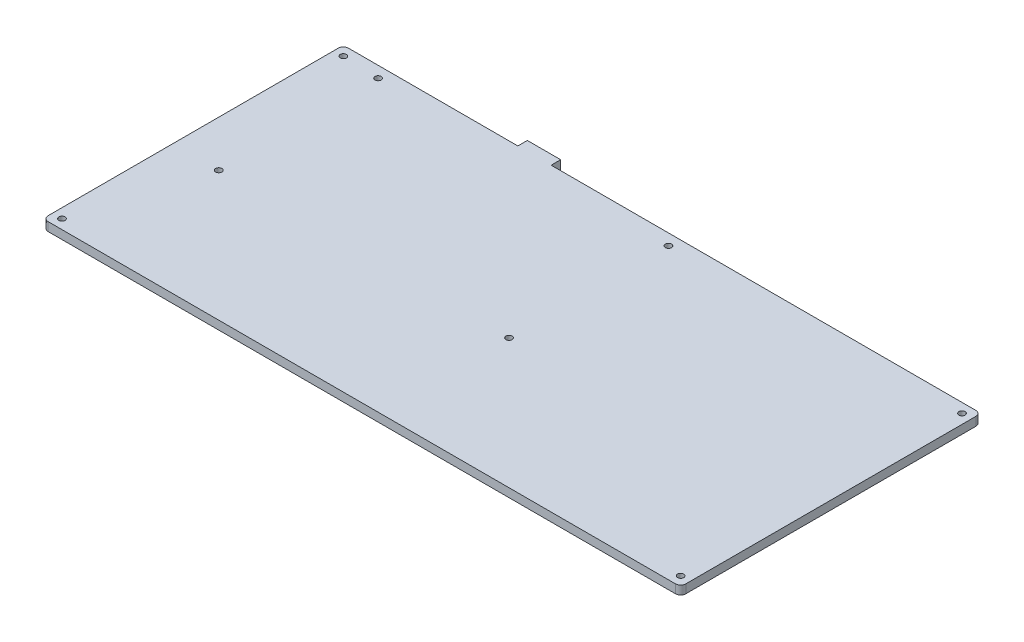
SolidWorks part; units mm, degrees
ref_plane "Front Plane" through (0, 0, 0) normal (0, 0, 1) x (1, 0, 0)
ref_plane "Top Plane" through (0, 0, 0) normal (0, 1, 0) x (1, 0, 0)
ref_plane "Right Plane" through (0, 0, 0) normal (1, 0, 0) x (0, 0, -1)
sketch "Croquis1" plane through (0, 0, 0) normal (0, 1, 0) x (1, 0, 0)
  line L0 (-90.6391, 36.4079) -> (-90.6391, 42.4079) construction
  line L1 (-90.3891, -43.2564) -> (94.1109, -43.2564)
  line L2 (-90.3891, -43.2564) -> (-90.3891, 43.6579)
  line L3 (-90.3891, 43.6579) -> (-39.9091, 43.6579)
  line L4 (94.1109, -43.2564) -> (94.1109, 43.6579)
  line L5 (94.3609, 42.4079) -> (94.3609, 36.4079) construction
  line L6 (92.8609, -43.5064) -> (86.8609, -43.5064) construction
  line L7 (-89.1391, 43.9079) -> (-83.1391, 43.9079) construction
  line L8 (-91.6391, 46.4079) -> (95.3609, 46.4079) construction
  line L9 (-39.9091, 43.6579) -> (-30.2691, 43.6579) construction
  line L10 (-39.9091, 43.6579) -> (-39.9091, 46.4079)
  line L11 (-39.9091, 46.4079) -> (-30.2691, 46.4079)
  line L12 (-30.2691, 43.6579) -> (-30.2691, 46.4079)
  line L13 (-40.1591, 43.9079) -> (-40.1591, 46.4079) construction
  line L14 (-30.0191, 43.9079) -> (-30.0191, 46.4079) construction
  line L15 (-39.9091, 43.6579) -> (-30.2691, 43.6579) construction
  line L16 (-30.2691, 43.6579) -> (94.1109, 43.6579)
  dimension "D1" = 0.25
  dimension "D2" = 0.25
  dimension "D3" = 0.25
  dimension "D4" = 0.25
  dimension "D5" = 0.25
  dimension "D6" = 0.25
extrude "Saliente-Extruir1" add sketch "Croquis1" along normal blind 2.5 contours L2 L3 L10 L11 L12 L16 L4 L1
fillet "Redondeo1" radius 1.5 4 edges at (94.1109, 1.25, 43.2564) (-90.3891, 1.25, 43.2564) (-90.3891, 1.25, -43.6579) (94.1109, 1.25, -43.6579)
sketch "Croquis5" plane through (0, 0, 0) normal (0, -1, 0) x (1, 0, 0)
  line L1 (-77.0891, 5.6961) -> (6.9109, 5.6961) construction
  line L2 (-77.0891, 5.6961) -> (-77.0891, -40.4079) construction
  line L3 (-77.0891, -40.4079) -> (6.9109, -40.4079) construction
  line L4 (6.9109, 5.6961) -> (6.9109, -40.4079) construction
hole_wizard "CSK for M1.6 Countersunk Flat Head Screw1" positions "Croquis3D1" profile "Croquis6" countersink size "M1.6" standard "ISO" end condition up to next
sketch3d "Croquis3D1"
  point P0 (-87.6391, 0, 40.5064)
  point P2 (91.3609, 0, 40.5064)
  point P4 (91.3609, 0, -40.9079)
  point P6 (-87.6391, 0, -40.9079)
  point P19 (-77.0891, 0, 5.6961)
  point P22 (6.9109, 0, 5.6961)
  point P25 (6.9109, 0, -40.4079)
  point P28 (-77.0891, 0, -40.4079)
sketch "Croquis6" plane through (-87.6391, 0, 40.5064) normal (1, 0, 0) x (0, 0, -1)
  line L0 (0, 0) -> (0, 2.5)
  line L1 (0, 2.5) -> (0.9, 2.5)
  line L2 (0.9, 2.5) -> (0.9, 0.9)
  line L3 (0.9, 0.9) -> (1.8, 0)
  line L5 (1.8, 0) -> (0, 0)
  line L6 (-0.9, 0.9) -> (-1.8, 0) construction
  line L11 (0, -6.35) -> (0, 107.95) construction
  dimension "Thru Hole Dia." = 1.8
  dimension "Thru Hole Depth" = 2.5
  dimension "Near C'Sink Dia." = 3.6
  dimension "Near C'Sink Angle" = 90
